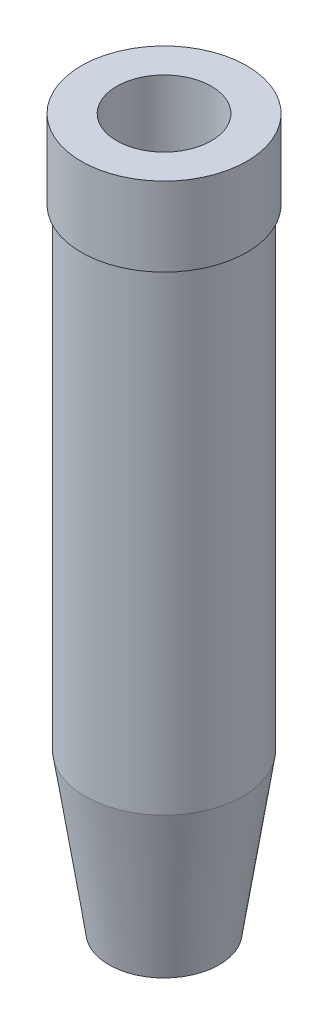
SolidWorks part; units mm, degrees
material "Aluminum Bronze"
ref_plane "Front Plane" through (0, 0, 0) normal (0, 0, 1) x (1, 0, 0)
ref_plane "Top Plane" through (0, 0, 0) normal (0, 1, 0) x (1, 0, 0)
ref_plane "Right Plane" through (0, 0, 0) normal (1, 0, 0) x (0, 0, -1)
sketch "Sketch1" plane through (0, 0, 0) normal (0, 0, 1) x (1, 0, 0)
  line L0 (0, 0) -> (0, 26.4721) construction
  line L1 (3, 0) -> (3, 45)
  line L2 (3, 45) -> (5.25, 45)
  line L3 (5.25, 45) -> (5.25, 40)
  line L4 (5.25, 40) -> (5, 40)
  line L5 (5, 40) -> (5, 10)
  line L7 (5, 10) -> (3.5, 0)
  line L8 (3.5, 0) -> (3, 0)
  dimension "D1" = 3
  dimension "D2" = 45
  dimension "D3" = 5
  dimension "D4" = 3.5
  dimension "D5" = 10
  dimension "D6" = 5
  dimension "D7" = 5.25
revolve "Revolve1" add sketch "Sketch1" angle 360 about L0
